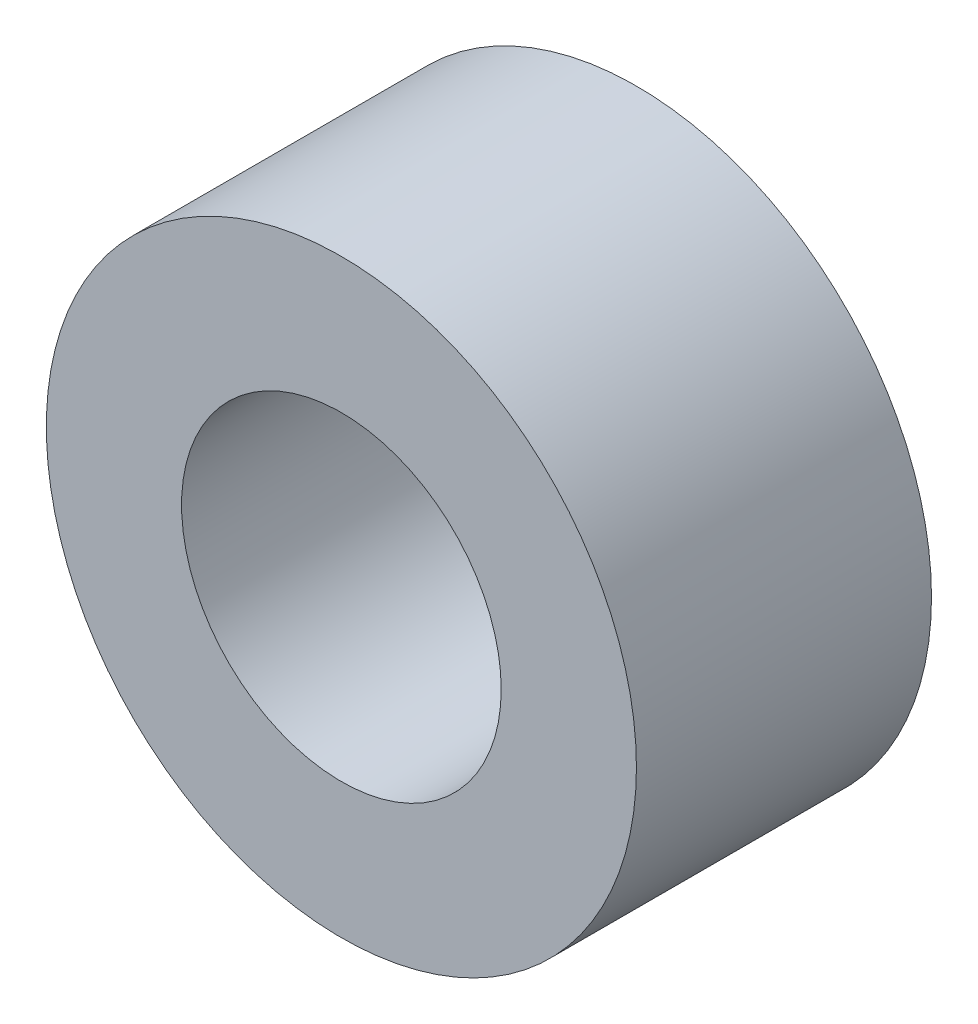
SolidWorks part; units mm, degrees
ref_plane "Alzado" through (0, 0, 0) normal (0, 0, 1) x (1, 0, 0)
ref_plane "Planta" through (0, 0, 0) normal (0, 1, 0) x (1, 0, 0)
ref_plane "Vista lateral" through (0, 0, 0) normal (1, 0, 0) x (0, 0, -1)
sketch "Croquis1" plane through (0, 0, 0) normal (0, 0, 1) x (1, 0, 0)
  circle A0 centre (0, 0) radius 3.25
  circle A1 centre (0, 0) radius 6
  dimension "D1" = 12
  dimension "D2" = 6.5
extrude "Saliente-Extruir1" add sketch "Croquis1" along normal blind 6
